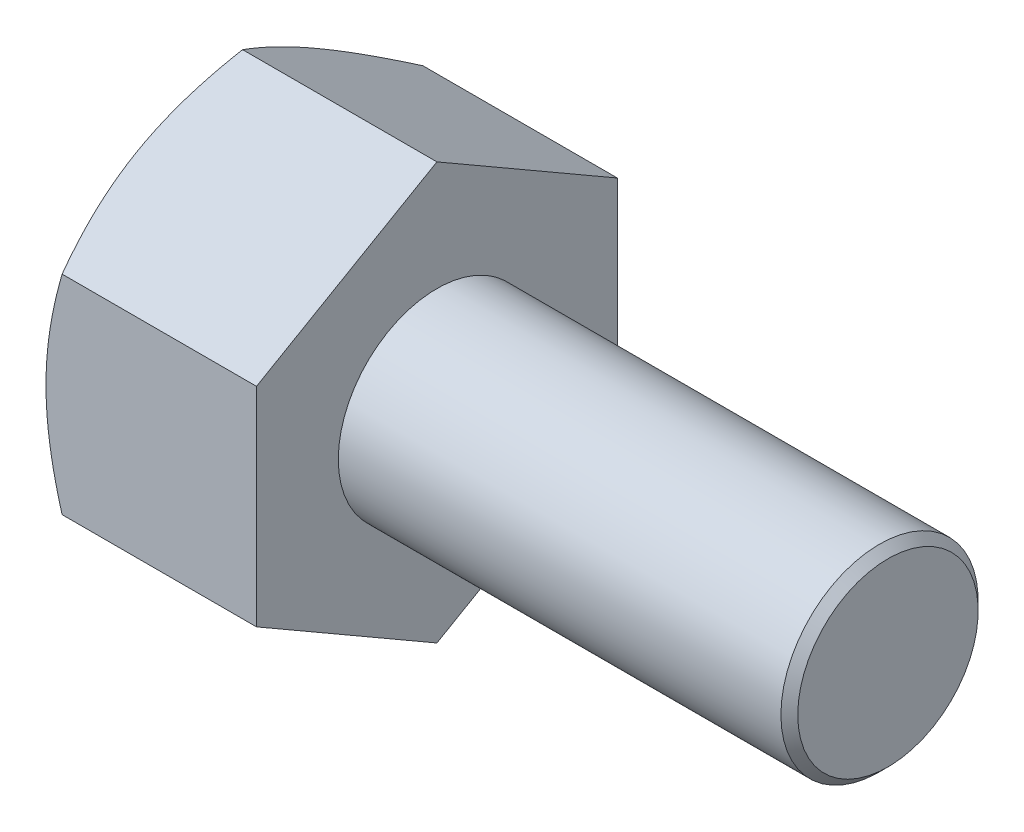
SolidWorks part; units mm, degrees
extrude "BaseHead" add sketch "Sketch1" along normal blind 17.78
sketch "Sketch1" plane through (0, 0, 0) normal (1, 0, 0) x (0, 0, -1)
  line L0 (15.24, 8.7988) -> (15.24, -8.7988)
  line L1 (-15.24, 8.7988) -> (-15.24, -8.7988)
  line L2 (15.24, -8.7988) -> (0, -17.5976)
  line L3 (0, -17.5976) -> (-15.24, -8.7988)
  line L4 (15.24, 8.7988) -> (0, 17.5976)
  line L5 (0, 17.5976) -> (-15.24, 8.7988)
  dimension "Width_flats" = 30.48
  dimension "D2" = 120
  dimension "D3" = 15.24
  dimension "D4" = 15.24
  dimension "D5" = 15.24
ref_plane "Plane1" through (0, 0, 0) normal (0, 0, 1) x (1, 0, 0)
ref_plane "Plane2" through (0, 0, 0) normal (0, 1, 0) x (1, 0, 0)
ref_plane "Plane3" through (0, 0, 0) normal (1, 0, 0) x (0, 0, -1)
sketch "BodySke" plane through (0, 0, 0) normal (0, 0, 1) x (1, 0, 0)
  line L0 (0, 8.7988) -> (0, -8.7988) construction
  line L1 (0, 0) -> (55.88, 0)
  line L2 (0, 0) -> (0, 8.3312)
  line L3 (0, 8.3312) -> (55.1688, 8.3312)
  line L4 (55.88, 0) -> (55.88, 7.62)
  line L5 (17.78, 17.5976) -> (17.78, 8.7988) construction
  line L6 (55.88, 7.62) -> (55.1688, 8.3312)
  line L7 (0, 0) -> (96.52, 0) construction
  line L8 (55.88, -7.62) -> (55.1688, -8.3312) construction
  line L9 (0, -8.3312) -> (55.1688, -8.3312) construction
  line L10 (19.8882, 15.24) -> (19.8882, -2.54) construction
  line L11 (24.13, 15.24) -> (24.13, -2.54) construction
  line L12 (17.78, 8.7988) -> (17.78, -8.7988) construction
  dimension "Diameter" = 16.6624
revolve "BaseBody" add sketch "BodySke" angle 360 about L7
cosmetic thread "ThreadCosmetic" [suppressed] parameters "Thread_length"=31.75, "Thread_minor"=15.24
sketch "Sketch3" plane through (0, 0, 0) normal (0, 0, 1) x (1, 0, 0)
  line L0 (0, 15.24) -> (5.0274, 23.9476)
  line L1 (0, 17.5976) -> (0, 8.7988) construction
  line L2 (5.0274, 23.9476) -> (5.0274, 30.2976)
  line L3 (5.0274, 30.2976) -> (-12.7, 30.2976)
  line L4 (-12.7, 30.2976) -> (-12.7, 15.24)
  line L5 (-12.7, 15.24) -> (0, 15.24)
  line L6 (0, 0) -> (99.06, 0) construction
  line L7 (17.78, 17.5976) -> (0, 17.5976) construction
  dimension "D1" = 15.24
  dimension "D2" = 6.35
  dimension "D3" = 12.7
  dimension "D4" = 6.35
  dimension "Head_ch_ang" = 30
revolve "HeadChamfer" cut sketch "Sketch3" angle 360 about L6
fillet "HeadFillet" [suppressed] radius 2.286
sketch "ThdSchSke" plane through (0, 0, 0) normal (0, 0, 1) x (1, 0, 0)
  line L0 (24.13, -7.62) -> (23.632, -8.3312)
  line L1 (24.13, -7.62) -> (24.628, -8.3312)
  line L2 (24.628, -8.3312) -> (24.628, -10.414)
  line L3 (-3.175, 0) -> (5.1513, 0) construction
  line L5 (24.628, -10.414) -> (23.632, -10.414)
  line L6 (23.632, -10.414) -> (23.632, -8.3312)
  dimension "Thread_minor" = 15.24
  dimension "Diameter" = 16.6624
  dimension "Start" = 24.13
revolve "ThreadSchematic" [suppressed] cut sketch "ThdSchSke" angle 360 about L3
pattern_linear "ThdSchPat" [suppressed]
equation "\"D3@Sketch1\" = \"Width_flats@Sketch1\" / 2"
equation "\"D4@Sketch1\" = \"D3@Sketch1\""
equation "\"D5@Sketch1\" = \"D4@Sketch1\""
equation "\"Thread_minor@ThreadCosmetic\" = \"Minor_dia@BodySke\""
equation "\"D1@Sketch3\" = \"Width_flats@Sketch1\" / 2"
equation "\"Thread_length@ThreadCosmetic\" = ((sgn( (\"Length@BodySke\" - \"Advance@BodySke\" ) - \"Thread_nom@BodySke\" )-1)*( (\"Length@BodySke\" - \"Advance@BodySke\" ) - \"Thread_nom@BodySke\" ))/-2+ \"Thread_nom@BodySke\""
equation "\"Thread_minor@ThdSchSke\" = \"Minor_dia@BodySke\""
equation "\"Diameter@ThdSchSke\" = \"Diameter@BodySke\""
equation "\"Overcut@ThdSchSke\" = \"Diameter@BodySke\" * 1.25"
equation "\"Start@ThdSchSke\" = \"Head_ht@BaseHead\" + \"Length@BodySke\" - \"Thread_length@ThreadCosmetic\"  '---Non-countersunk---"
equation "\"Num_threads@ThdSchPat\" = int( \"Thread_length@ThreadCosmetic\" / \"Advance@BodySke\" + 0.999 )  + 1"
equation "\"Advance@ThdSchPat\" = \"Thread_length@ThreadCosmetic\" /  (\"Num_threads@ThdSchPat\" - 1) 'relax it"
equation "\"Num_threads@ThdSchPat\" = \"Num_threads@ThdSchPat\" - sgn( \"Num_threads@ThdSchPat\" - 1) '---chamfered tips only---"
